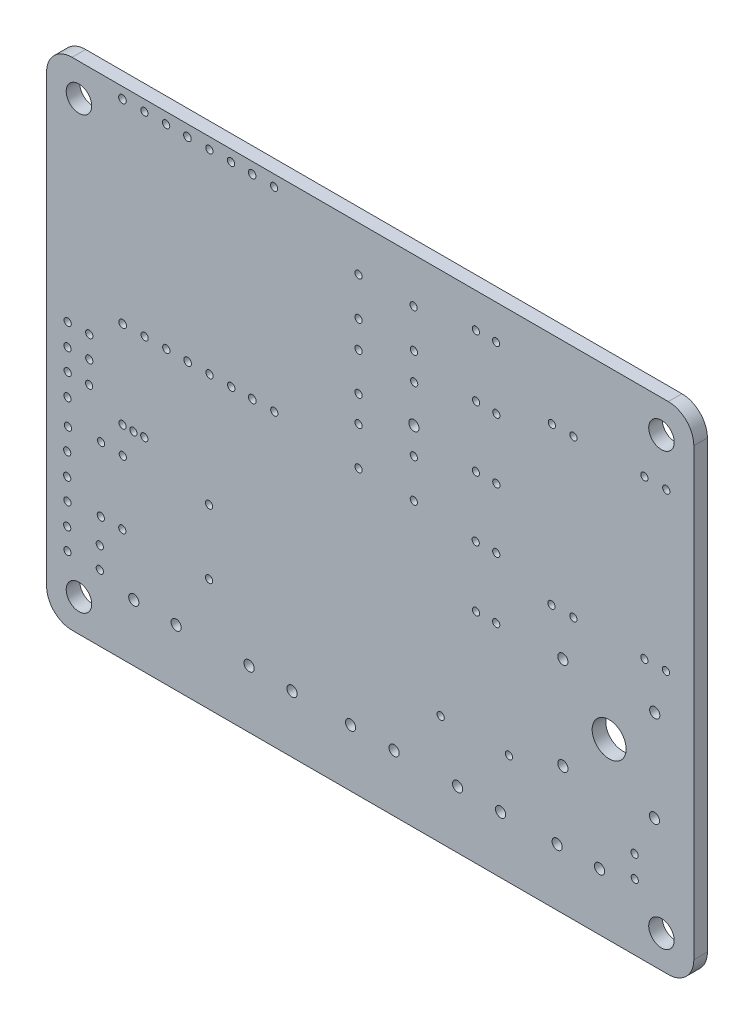
SolidWorks part; units mm, degrees
ref_plane "Plan de face" through (0, 0, 0) normal (0, 0, 1) x (1, 0, 0)
ref_plane "Plan de dessus" through (0, 0, 0) normal (0, 1, 0) x (1, 0, 0)
ref_plane "Plan de droite" through (0, 0, 0) normal (1, 0, 0) x (0, 0, -1)
sketch "Esquisse1" plane through (0, 0, 0) normal (0, 0, 1) x (1, 0, 0)
  line L0 (2.5789, 55.9993) -> (78.7789, 55.9993) construction
  line L1 (2.6204, 0.4796) -> (78.8204, 58.8996) construction
  line L2 (5.6204, 58.8996) -> (75.8204, 58.8996)
  line L3 (2.6204, 55.8996) -> (2.6204, 3.4796)
  line L4 (5.6204, 0.4796) -> (75.8204, 0.4796)
  line L5 (78.8204, 55.8996) -> (78.8204, 3.4796)
  line L7 (75.0104, 4.2896) -> (6.4304, 4.2896) construction
  line L8 (75.0104, 4.2896) -> (75.0104, 55.0896) construction
  line L9 (75.0104, 55.0896) -> (6.4304, 55.0896) construction
  line L10 (6.4304, 4.2896) -> (6.4304, 55.0896) construction
  line L11 (75.0104, 4.2896) -> (6.4304, 55.0896) construction
  line L12 (75.0104, 55.0896) -> (6.4304, 4.2896) construction
  circle A0 centre (6.4304, 55.0896) radius 1.5
  circle A1 centre (75.0104, 4.2896) radius 1.5
  circle A2 centre (6.4304, 4.2896) radius 1.5
  circle A3 centre (75.0104, 55.0896) radius 1.5
  arc A4 (2.6204, 3.4796) -> (5.6204, 0.4796) centre (5.6204, 3.4796) ccw
  arc A5 (75.8204, 0.4796) -> (78.8204, 3.4796) centre (75.8204, 3.4796) ccw
  arc A6 (75.8204, 58.8996) -> (78.8204, 55.8996) centre (75.8204, 55.8996) cw
  arc A7 (5.6204, 58.8996) -> (2.6204, 55.8996) centre (5.6204, 55.8996) ccw
  circle A8 centre (11.5528, 57.6154) radius 0.4491
  circle A9 centre (14.1371, 57.6154) radius 0.4253
  circle A10 centre (16.6886, 57.6154) radius 0.4321
  circle A11 centre (19.1996, 57.5827) radius 0.4491
  circle A12 centre (21.7839, 57.5827) radius 0.4253
  circle A13 centre (24.3354, 57.5827) radius 0.4321
  circle A14 centre (26.8216, 57.5827) radius 0.4491
  circle A15 centre (29.4058, 57.5827) radius 0.4253
  circle A16 centre (11.575, 34.708) radius 0.4491
  circle A17 centre (14.1593, 34.708) radius 0.4253
  circle A18 centre (16.7108, 34.708) radius 0.4321
  circle A19 centre (19.2218, 34.6753) radius 0.4491
  circle A20 centre (21.8061, 34.6753) radius 0.4253
  circle A21 centre (24.3576, 34.6753) radius 0.4321
  circle A22 centre (26.8438, 34.6753) radius 0.4491
  circle A23 centre (29.428, 34.6753) radius 0.4253
  circle A24 centre (53.1633, 54.8323) radius 0.4253
  circle A25 centre (55.5404, 54.8323) radius 0.4253
  circle A26 centre (55.5701, 47.5226) radius 0.4253
  circle A27 centre (53.193, 47.6117) radius 0.4253
  circle A28 centre (53.1633, 40.4209) radius 0.4253
  circle A29 centre (55.5701, 40.4209) radius 0.4253
  circle A30 centre (53.1414, 33.299) radius 0.4253
  circle A31 centre (55.5571, 33.3399) radius 0.4253
  circle A32 centre (55.5571, 26.1749) radius 0.4253
  circle A33 centre (53.1824, 26.1749) radius 0.4253
  circle A34 centre (62.067, 31.2928) radius 0.4253
  circle A35 centre (64.6464, 31.2928) radius 0.4253
  circle A36 centre (72.9987, 31.2518) radius 0.4253
  circle A37 centre (75.5371, 31.2928) radius 0.4253
  circle A38 centre (75.5781, 49.7989) radius 0.4253
  circle A39 centre (72.9987, 49.8399) radius 0.4253
  circle A40 centre (64.6464, 49.758) radius 0.4253
  circle A41 centre (62.1079, 49.758) radius 0.4253
  circle A42 centre (49.0188, 13.4408) radius 0.4253
  circle A43 centre (57.05, 13.4408) radius 0.4253
  circle A44 centre (5.1029, 31.6564) radius 0.4253
  circle A45 centre (7.6434, 31.6778) radius 0.4253
  circle A46 centre (7.6434, 29.1159) radius 0.4253
  circle A47 centre (7.6221, 26.5113) radius 0.4253
  circle A48 centre (5.1029, 26.554) radius 0.4253
  circle A49 centre (5.0816, 29.0732) radius 0.4253
  circle A50 centre (5.0816, 23.9708) radius 0.4253
  circle A51 centre (11.5649, 24.4178) radius 0.4253
  circle A52 centre (12.8451, 24.3582) radius 0.4253
  circle A53 centre (14.1254, 24.4178) radius 0.4253
  circle A54 centre (5.1341, 20.9939) radius 0.4253
  circle A55 centre (5.0448, 18.4335) radius 0.4253
  circle A56 centre (5.0448, 15.8433) radius 0.4253
  circle A57 centre (5.0745, 13.3424) radius 0.4253
  circle A58 centre (5.0448, 10.782) radius 0.4253
  circle A59 centre (5.0745, 8.2811) radius 0.4253
  circle A60 centre (9.0045, 13.7592) radius 0.4253
  circle A61 centre (9.0343, 21.381) radius 0.4253
  circle A62 centre (11.5947, 21.2619) radius 0.4253
  circle A63 centre (21.7471, 21.3512) radius 0.4253
  circle A64 centre (21.7471, 13.7592) radius 0.4253
  circle A65 centre (11.5352, 13.7295) radius 0.4253
  circle A66 centre (8.8854, 10.782) radius 0.4253
  circle A67 centre (8.8854, 8.2811) radius 0.4253
  circle A68 centre (39.3486, 53.6194) radius 0.4253
  circle A69 centre (45.8304, 53.6194) radius 0.4253
  circle A70 centre (45.8636, 49.0987) radius 0.4253
  circle A71 centre (39.3486, 49.0987) radius 0.4253
  circle A72 centre (39.3486, 45.9409) radius 0.4253
  circle A73 centre (45.8969, 45.9077) radius 0.4253
  circle A74 centre (45.8636, 41.4867) radius 0.6
  circle A75 centre (39.3486, 41.4535) radius 0.4253
  circle A76 centre (45.8563, 38.3454) radius 0.4253
  circle A77 centre (39.3501, 38.3709) radius 0.4253
  circle A78 centre (39.3501, 33.8588) radius 0.4253
  circle A79 centre (45.8563, 33.8077) radius 0.4253
  circle A80 centre (71.8527, 10.8069) radius 0.4253
  circle A81 centre (71.87, 8.252) radius 0.4253
  circle A82 centre (12.887, 7.2174) radius 0.6
  circle A83 centre (17.8761, 7.1603) radius 0.6
  circle A84 centre (26.4617, 7.2875) radius 0.6
  circle A85 centre (31.5217, 7.2222) radius 0.6
  circle A86 centre (38.4097, 7.2222) radius 0.6
  circle A87 centre (43.5349, 7.1896) radius 0.6
  circle A88 centre (51.0105, 7.2549) radius 0.6
  circle A89 centre (56.0704, 7.1896) radius 0.6
  circle A90 centre (62.7299, 7.2222) radius 0.6
  circle A91 centre (67.7245, 7.2222) radius 0.6
  circle A92 centre (63.4046, 26.428) radius 0.6
  circle A93 centre (74.2221, 26.3899) radius 0.6
  circle A94 centre (74.184, 15.6105) radius 0.6
  circle A95 centre (63.4046, 15.5343) radius 0.6
  circle A96 centre (68.8515, 20.9811) radius 2
  point P6 (40.7204, 29.6896)
  point P26 (2.6204, 58.8996)
  point P32 (16.6886, 57.6154)
  point P45 (0, 0)
  point P148 (8.8854, 10.782)
  point P149 (8.8854, 8.2811)
  point P152 (39.3486, 53.6194)
  dimension "D4" = 3
  dimension "D7" = 3
  dimension "D1" = 76.2
  dimension "D2" = 76.2
  dimension "D3" = 58.42
  dimension "D5" = 68.58
  dimension "D6" = 50.8
extrude "Boss.-Extru.1" add sketch "Esquisse1" along normal blind 1.6
